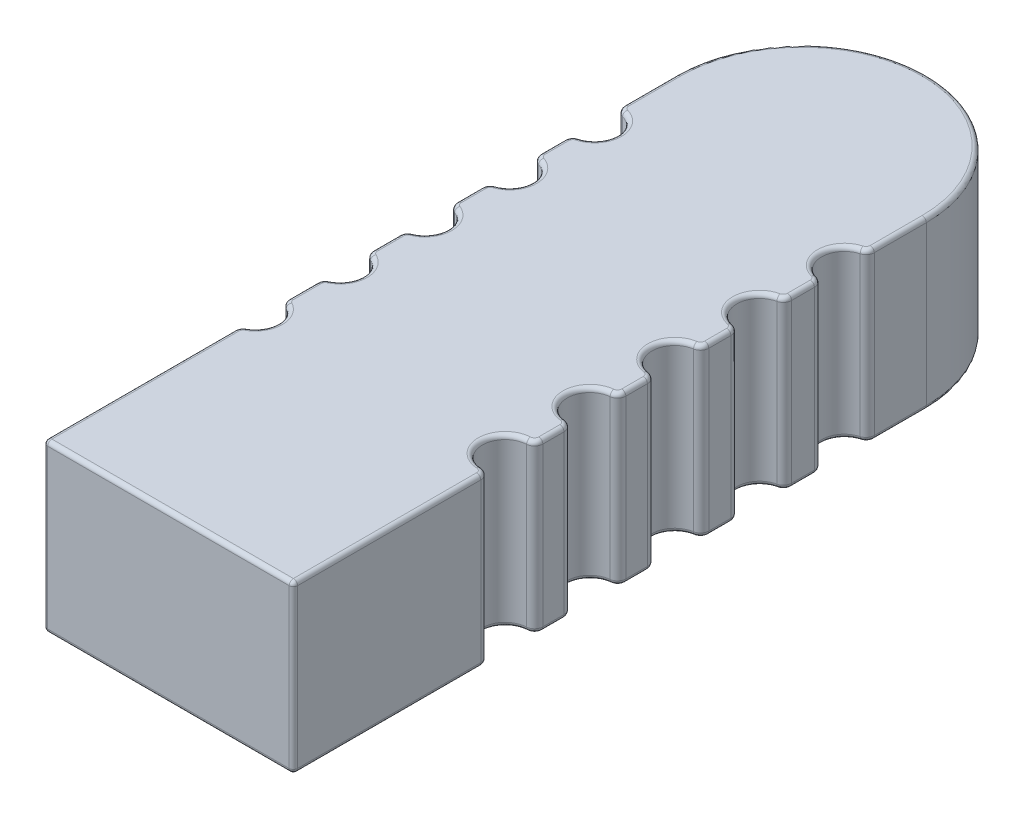
SolidWorks part; units mm, degrees
ref_plane "Front Plane" through (0, 0, 0) normal (0, 0, 1) x (1, 0, 0)
ref_plane "Top Plane" through (0, 0, 0) normal (0, 1, 0) x (1, 0, 0)
ref_plane "Right Plane" through (0, 0, 0) normal (1, 0, 0) x (0, 0, -1)
sketch "Sketch1" plane through (0, 0, 0) normal (0, 1, 0) x (1, 0, 0)
  line L0 (0, 0) -> (0, 104.4802) construction
  line L1 (-19.05, 0) -> (19.05, 0)
  line L2 (19.05, 0) -> (19.05, 28.575)
  line L3 (-19.05, 0) -> (-19.05, 29.1559)
  line L4 (19.05, 88.5926) -> (19.05, 96.52)
  line L5 (19.05, 75.9762) -> (19.05, 79.4595)
  line L6 (19.05, 63.3452) -> (19.05, 66.7169)
  line L7 (19.05, 50.7) -> (19.05, 53.9889)
  line L8 (19.05, 38.041) -> (19.05, 41.275)
  line L9 (-19.05, 37.4601) -> (-19.05, 41.7054)
  line L10 (-19.05, 50.2697) -> (-19.05, 54.2733)
  line L11 (-19.05, 63.0607) -> (-19.05, 66.8584)
  line L12 (-19.05, 75.8347) -> (-19.05, 79.4595)
  line L13 (-19.05, 88.5926) -> (-19.05, 96.52)
  arc A0 (18.1203, 80.6831) -> (18.1203, 87.369) centre (19.05, 84.026) cw
  arc A1 (-18.1203, 80.6831) -> (-18.1203, 87.369) centre (-19.05, 84.026) ccw
  arc A2 (18.0522, 67.9574) -> (18.0522, 74.7357) centre (18.796, 71.3465) cw
  arc A3 (-18.1883, 68.061) -> (-18.1883, 74.6321) centre (-19.304, 71.3465) ccw
  arc A4 (17.9842, 55.2423) -> (17.9842, 62.0917) centre (18.542, 58.667) cw
  arc A5 (-18.2564, 55.4506) -> (-18.2564, 61.8835) centre (-19.558, 58.667) ccw
  arc A6 (17.9161, 42.5377) -> (17.9161, 49.4374) centre (18.288, 45.9875) cw
  arc A7 (-18.3245, 42.8527) -> (-18.3245, 49.1223) centre (-19.812, 45.9875) ccw
  arc A8 (17.8481, 29.8432) -> (17.8481, 36.7728) centre (18.034, 33.308) cw
  arc A9 (-18.3925, 30.2684) -> (-18.3925, 36.3476) centre (-20.066, 33.308) ccw
  arc A10 (-19.05, 96.52) -> (19.05, 96.52) centre (0, 96.52) cw
  arc A11 (-18.1203, 87.369) -> (-19.05, 88.5926) centre (-17.78, 88.5926) cw
  arc A12 (-18.1203, 80.6831) -> (-19.05, 79.4595) centre (-17.78, 79.4595) ccw
  arc A13 (-18.1883, 74.6321) -> (-19.05, 75.8347) centre (-17.78, 75.8347) cw
  arc A14 (-18.1883, 68.061) -> (-19.05, 66.8584) centre (-17.78, 66.8584) ccw
  arc A15 (-18.2564, 61.8835) -> (-19.05, 63.0607) centre (-17.78, 63.0607) cw
  arc A16 (-18.2564, 55.4506) -> (-19.05, 54.2733) centre (-17.78, 54.2733) ccw
  arc A17 (-18.3245, 49.1223) -> (-19.05, 50.2697) centre (-17.78, 50.2697) cw
  arc A18 (-18.3245, 42.8527) -> (-19.05, 41.7054) centre (-17.78, 41.7054) ccw
  arc A19 (-18.3925, 36.3476) -> (-19.05, 37.4601) centre (-17.78, 37.4601) cw
  arc A20 (-18.3925, 30.2684) -> (-19.05, 29.1559) centre (-17.78, 29.1559) ccw
  arc A21 (18.1203, 87.369) -> (19.05, 88.5926) centre (17.78, 88.5926) ccw
  arc A22 (18.1203, 80.6831) -> (19.05, 79.4595) centre (17.78, 79.4595) cw
  arc A23 (18.0522, 74.7357) -> (19.05, 75.9762) centre (17.78, 75.9762) ccw
  arc A24 (18.0522, 67.9574) -> (19.05, 66.7169) centre (17.78, 66.7169) cw
  arc A25 (17.9842, 62.0917) -> (19.05, 63.3452) centre (17.78, 63.3452) ccw
  arc A26 (17.9842, 55.2423) -> (19.05, 53.9889) centre (17.78, 53.9889) cw
  arc A27 (17.9161, 49.4374) -> (19.05, 50.7) centre (17.78, 50.7) ccw
  arc A28 (17.9161, 42.5377) -> (19.05, 41.275) centre (17.78, 41.275) cw
  arc A29 (17.8481, 36.7728) -> (19.05, 38.041) centre (17.78, 38.041) ccw
  arc A30 (17.8481, 29.8432) -> (19.05, 28.575) centre (17.78, 28.575) cw
  point P40 (-19.05, 87.4959)
  point P43 (-19.05, 80.5562)
  point P62 (19.05, 87.4959)
  point P65 (19.05, 80.5562)
  dimension "D1" = 1.27
  dimension "D3" = 3.4698
  dimension "D4" = 0.254
  dimension "D5" = 28.575
  dimension "D6" = 41.275
  dimension "D2" = 38.1
  dimension "D45" = 96.52
extrude "Extrude1" add sketch "Sketch1" along normal blind 25.4
fillet "Fillet1" radius 0.635 90 edges at (19.05, 0, -14.2875) (18.7018, 0, -29.4486) (14.5642, 0, -33.308) (18.7018, 0, -37.1674) (19.05, 0, -39.658) (18.7249, 0, -42.1235) (14.8182, 0, -45.9875) (18.7249, 0, -49.8515) (19.05, 0, -52.3444) (18.7475, 0, -54.8115) (15.0722, 0, -58.667) (18.7475, 0, -62.5225) (19.05, 0, -65.031) (18.7696, 0, -67.5129) (15.3262, 0, -71.3465) (18.7696, 0, -75.1802) (19.05, 0, -77.7179) (18.7912, 0, -80.2279) (15.5802, 0, -84.026) (18.7912, 0, -87.8242) (19.05, 0, -92.5563) (0, 0, -115.57) (-19.05, 0, -92.5563) (-18.7912, 0, -87.8242) (-15.5802, 0, -84.026) (-18.7912, 0, -80.2279) (-19.05, 0, -77.6471) (-18.8124, 0, -75.095) (-15.8342, 0, -71.3465) (-18.8124, 0, -67.5981) (-19.05, 0, -64.9596) (-18.8331, 0, -62.3508) (-16.0882, 0, -58.667) (-18.8331, 0, -54.9832) (-19.05, 0, -52.2715) (-18.8534, 0, -49.5909) (-16.3422, 0, -45.9875) (-18.8534, 0, -42.3841) (-19.05, 0, -39.5827) (-18.8733, 0, -36.814) (-16.5962, 0, -33.308) (-18.8733, 0, -29.802) (-19.05, 0, -14.5779) (0, 0, 0) (19.05, 25.4, -14.2875) (18.7018, 25.4, -29.4486) (14.5642, 25.4, -33.308) (18.7018, 25.4, -37.1674) (19.05, 25.4, -39.658) (18.7249, 25.4, -42.1235) (14.8182, 25.4, -45.9875) (18.7249, 25.4, -49.8515) (19.05, 25.4, -52.3444) (18.7475, 25.4, -54.8115) (15.0722, 25.4, -58.667) (18.7475, 25.4, -62.5225) (19.05, 25.4, -65.031) (18.7696, 25.4, -67.5129) (15.3262, 25.4, -71.3465) (18.7696, 25.4, -75.1802) (19.05, 25.4, -77.7179) (18.7912, 25.4, -80.2279) (15.5802, 25.4, -84.026) (18.7912, 25.4, -87.8242) (19.05, 25.4, -92.5563) (0, 25.4, -115.57) (-19.05, 25.4, -92.5563) (-18.7912, 25.4, -87.8242) (-15.5802, 25.4, -84.026) (-18.7912, 25.4, -80.2279) (-19.05, 25.4, -77.6471) (-18.8124, 25.4, -75.095) (-15.8342, 25.4, -71.3465) (-18.8124, 25.4, -67.5981) (-19.05, 25.4, -64.9596) (-18.8331, 25.4, -62.3508) (-16.0882, 25.4, -58.667) (-18.8331, 25.4, -54.9832) (-19.05, 25.4, -52.2715) (-18.8534, 25.4, -49.5909) (-16.3422, 25.4, -45.9875) (-18.8534, 25.4, -42.3841) (-19.05, 25.4, -39.5827) (-18.8733, 25.4, -36.814) (-16.5962, 25.4, -33.308) (-18.8733, 25.4, -29.802) (-19.05, 25.4, -14.5779) (0, 25.4, 0) (19.05, 12.7, 0) (-19.05, 12.7, 0)
